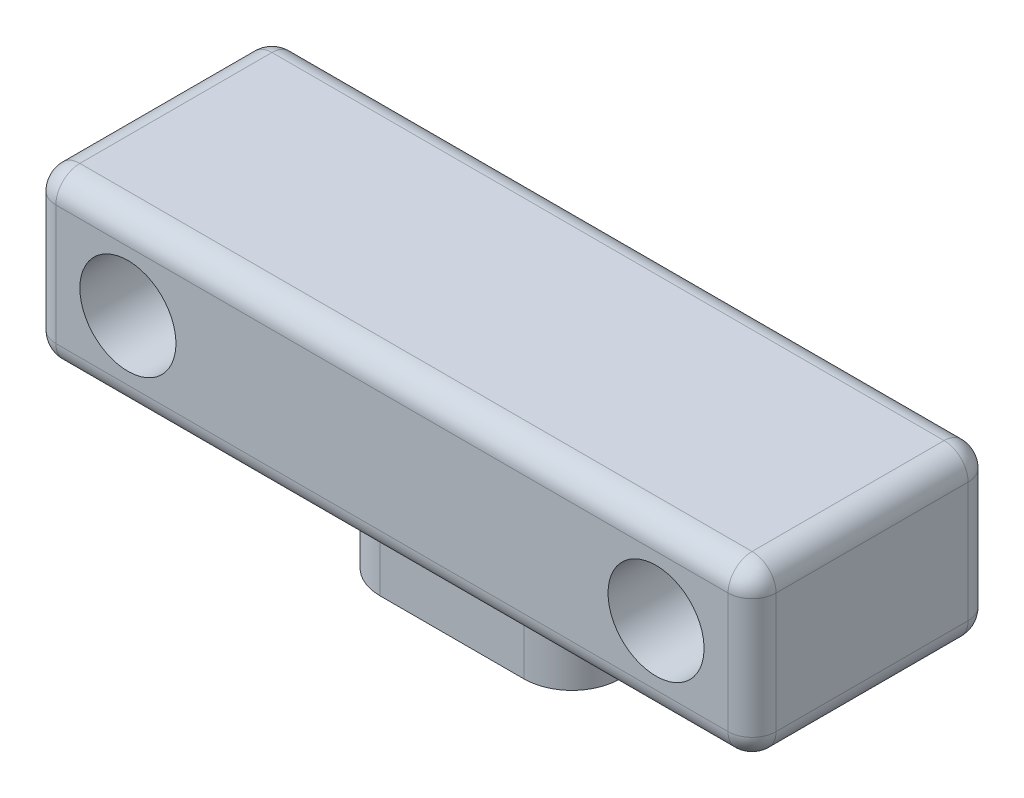
SolidWorks part; units mm, degrees
material "Aluminum 6061-T6"
ref_plane "Front Plane" through (0, 0, 0) normal (0, 0, 1) x (1, 0, 0)
ref_plane "Top Plane" through (0, 0, 0) normal (0, 1, 0) x (1, 0, 0)
ref_plane "Right Plane" through (0, 0, 0) normal (1, 0, 0) x (0, 0, -1)
sketch "Sketch1" plane through (0, 0, 0) normal (0, 1, 0) x (1, 0, 0)
  circle A0 centre (0, 0) radius 2
  dimension "D1" = 4
extrude "Boss-Extrude1" add sketch "Sketch1" along normal blind 1.85 and the other way blind 2
sketch "Sketch2" plane through (0, -2, 0) normal (0, -1, 0) x (1, 0, 0)
  circle A0 centre (0, 0) radius 2
  dimension "D1" = 4
sketch "Sketch3" plane through (0, 1.85, 0) normal (0, 1, 0) x (1, 0, 0)
  line L1 (-15, 5) -> (15, 5)
  line L2 (-15, 5) -> (-15, -5)
  line L3 (-15, -5) -> (15, -5)
  line L4 (15, 5) -> (15, -5)
  line L5 (-15, 5) -> (15, -5) construction
  line L6 (-15, -5) -> (15, 5) construction
  point P0 (0, 0)
  dimension "D1" = 30
  dimension "D2" = 10
extrude "Boss-Extrude3" add sketch "Sketch3" along normal blind 7
sketch "Sketch4" plane through (0, 8.85, 0) normal (0, 1, 0) x (1, 0, 0)
sketch "Sketch7" plane through (0, -2, 0) normal (0, -1, 0) x (1, 0, 0)
  line L1 (-5, 2.5) -> (5, 2.5)
  line L2 (-5, 2.5) -> (-5, -2.5)
  line L3 (-5, -2.5) -> (5, -2.5)
  line L4 (5, 2.5) -> (5, -2.5)
  line L5 (-5, 2.5) -> (5, -2.5) construction
  line L6 (-5, -2.5) -> (5, 2.5) construction
  point P0 (0, 0)
  dimension "D1" = 10
  dimension "D2" = 5
extrude "Boss-Extrude7" add sketch "Sketch7" against normal blind 2
fillet "Fillet2" radius 2 4 edges at (5, -1, -2.5) (5, -1, 2.5) (-5, -1, -2.5) (-5, -1, 2.5)
sketch "Sketch9" plane through (0, 0, -5) normal (0, 0, -1) x (-1, 0, 0)
  line L0 (-15, 8.85) -> (-15, 1.85) construction
  line L1 (-15, 1.85) -> (15, 1.85) construction
  line L2 (0, 13.6648) -> (0, -7.8078) construction
  circle A0 centre (-11, 5.35) radius 2
  circle A1 centre (11, 5.35) radius 2
  dimension "D1" = 4
  dimension "D2" = 4
  dimension "D3" = 3.5
extrude "Cut-Extrude3" cut sketch "Sketch9" against normal up to surface (10 mm away) up to face at (0, 5.35, 5)
fillet "Fillet3" radius 1 12 edges at (0, 8.85, 5) (0, 1.85, 5) (15, 5.35, 5) (15, 8.85, 0) (15, 1.85, 0) (15, 5.35, -5) (0, 8.85, -5) (0, 1.85, -5) (-15, 5.35, -5) (-15, 8.85, 0) (-15, 5.35, 5) (-15, 1.85, 0)
